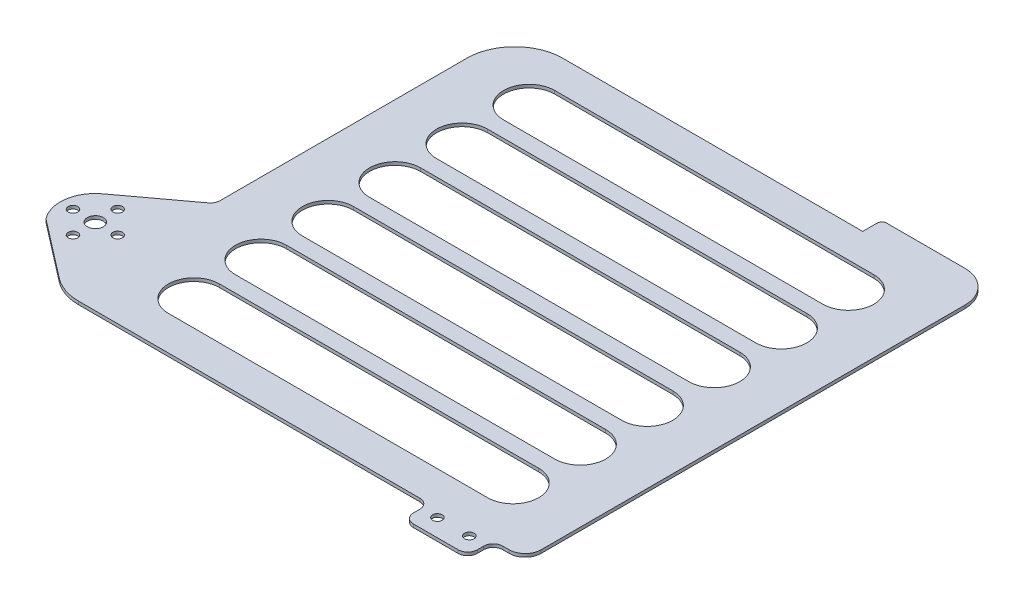
SolidWorks part; units mm, degrees
material "A-玻璃纤维"
ref_plane "前视基准面" through (0, 0, 0) normal (0, 0, 1) x (1, 0, 0)
ref_plane "上视基准面" through (0, 0, 0) normal (0, 1, 0) x (1, 0, 0)
ref_plane "右视基准面" through (0, 0, 0) normal (1, 0, 0) x (0, 0, -1)
sketch "草图1" plane through (0, 0, 0) normal (0, 1, 0) x (1, 0, 0)
  line L1 (-72.5, 70.87) -> (72.5, 70.87)
  line L2 (-72.5, 70.87) -> (-72.5, -70.87)
  line L3 (-72.5, -70.87) -> (72.5, -70.87)
  line L4 (72.5, 70.87) -> (72.5, -70.87)
  line L5 (0, -70.87) -> (0, 70.87) construction
  line L6 (-72.5, 0) -> (72.5, 0) construction
  point P0 (0, 0)
  dimension "D1" = 145
  dimension "D2" = 141.74
extrude "凸台-拉伸1" add sketch "草图1" along normal blind 1
fillet "圆角1" radius 15 1 edges at (-72.5, 0.5, -70.87)
sketch "草图2" plane through (0, 1, 0) normal (0, 1, 0) x (1, 0, 0)
  line L0 (-72.5, -70.87) -> (72.5, -70.87) construction
  line L1 (-72.5, 55.87) -> (-72.5, -70.87) construction
  line L2 (-92.7479, -37.9812) -> (-72.5, -22.9812)
  line L3 (-94.8039, -53.6736) -> (-72.5, -81.6736)
  line L4 (-72.5, -22.9812) -> (-72.5, -81.6736)
  arc A0 (-92.7479, -37.9812) -> (-94.8039, -53.6736) centre (-86.2, -46.82) ccw
  dimension "D1" = 24.05
  dimension "D2" = 13.7
  dimension "D3" = 22
  dimension "D4" = 15
  dimension "D5" = 28
extrude "凸台-拉伸2" add sketch "草图2" against normal blind 1
sketch "草图3" plane through (0, 1, 0) normal (0, 1, 0) x (1, 0, 0)
  circle A0 centre (-86.2, -46.82) radius 2.5
  circle A1 centre (-93.2, -46.82) radius 1.5
  dimension "D1" = 5
  dimension "D2" = 3
  dimension "D3" = 7
extrude "切除-拉伸1" cut sketch "草图3" against normal through all
pattern_circular "阵列(圆周)1" count 4 over 360 about axis through (-86.2, 0, 46.82) along (0, 1, 0) of "切除-拉伸1"
sketch "草图4" plane through (0, 1, 0) normal (0, 1, 0) x (1, 0, 0)
  line L0 (-72.5, -70.87) -> (-94.8039, -53.6736)
  line L1 (-94.8039, -53.6736) -> (-72.5, -88.8628)
  line L2 (-72.5, -88.8628) -> (-72.5, -70.87)
  dimension "D1" = 20
extrude "切除-拉伸2" cut sketch "草图4" against normal through all
fillet "圆角2" radius 15 1 edges at (-72.5, 0.5, 70.87)
fillet "圆角3" radius 3 1 edges at (-72.5, 0.5, 22.9812)
sketch "草图5" plane through (0, 1, 0) normal (0, 1, 0) x (1, 0, 0)
  line L0 (-50, 52.87) -> (50, 52.87) construction
  line L1 (-50, 60.87) -> (50, 60.87)
  line L2 (-50, 44.87) -> (50, 44.87)
  line L3 (72.5, 70.87) -> (-57.5, 70.87) construction
  line L4 (-50, 31.87) -> (50, 31.87) construction
  line L5 (-50, 39.87) -> (50, 39.87)
  line L6 (-50, 23.87) -> (50, 23.87)
  line L7 (-50, 10.87) -> (50, 10.87) construction
  line L8 (-50, 18.87) -> (50, 18.87)
  line L9 (-50, 2.87) -> (50, 2.87)
  line L10 (-50, -10.13) -> (50, -10.13) construction
  line L11 (-50, -2.13) -> (50, -2.13)
  line L12 (-50, -18.13) -> (50, -18.13)
  line L13 (-50, -31.13) -> (50, -31.13) construction
  line L14 (-50, -23.13) -> (50, -23.13)
  line L15 (-50, -39.13) -> (50, -39.13)
  line L16 (-50, -52.13) -> (50, -52.13) construction
  line L17 (-50, -44.13) -> (50, -44.13)
  line L18 (-50, -60.13) -> (50, -60.13)
  arc A0 (-50, 60.87) -> (-50, 44.87) centre (-50, 52.87) ccw
  arc A1 (50, 44.87) -> (50, 60.87) centre (50, 52.87) ccw
  arc A2 (-50, 39.87) -> (-50, 23.87) centre (-50, 31.87) ccw
  arc A3 (50, 23.87) -> (50, 39.87) centre (50, 31.87) ccw
  arc A4 (-50, 18.87) -> (-50, 2.87) centre (-50, 10.87) ccw
  arc A5 (50, 2.87) -> (50, 18.87) centre (50, 10.87) ccw
  arc A6 (-50, -2.13) -> (-50, -18.13) centre (-50, -10.13) ccw
  arc A7 (50, -18.13) -> (50, -2.13) centre (50, -10.13) ccw
  arc A8 (-50, -23.13) -> (-50, -39.13) centre (-50, -31.13) ccw
  arc A9 (50, -39.13) -> (50, -23.13) centre (50, -31.13) ccw
  arc A10 (-50, -44.13) -> (-50, -60.13) centre (-50, -52.13) ccw
  arc A11 (50, -60.13) -> (50, -44.13) centre (50, -52.13) ccw
  point P2 (0, 52.87)
  point P14 (0, 31.87)
  point P21 (0, 10.87)
  point P28 (0, -10.13)
  point P35 (0, -31.13)
  point P42 (0, -52.13)
  dimension "D1" = 100
  dimension "D2" = 10
  dimension "D3" = 16
  dimension "D4" = 6
extrude "切除-拉伸3" cut sketch "草图5" against normal through all
sketch "草图6" plane through (0, 0, -70.87) normal (0, 0, -1) x (-1, 0, 0)
  line L0 (-72.5, 1) -> (57.5, 1) construction
  line L1 (-72.5, 0) -> (-36.5, 0)
  line L2 (-72.5, 0) -> (-72.5, 1)
  line L3 (-72.5, 1) -> (-36.5, 1)
  line L4 (-36.5, 0) -> (-36.5, 1)
  dimension "D1" = 36
extrude "凸台-拉伸3" add sketch "草图6" along normal blind 6
fillet "圆角4" radius 10 1 edges at (72.5, 0.5, -76.87)
fillet "圆角5" radius 1.5 1 edges at (36.5, 0.5, -76.87)
sketch "草图8" plane through (0, 1, 0) normal (0, 1, 0) x (1, 0, 0)
  line L0 (72.5, -70.87) -> (72.5, 66.87) construction
  line L1 (62.5, -70.87) -> (42.5, -70.87)
  line L2 (62.5, -70.87) -> (62.5, -78.87)
  line L3 (62.5, -78.87) -> (42.5, -78.87)
  line L4 (42.5, -70.87) -> (42.5, -78.87)
  line L5 (-67.3889, -70.87) -> (72.5, -70.87) construction
  circle A0 centre (47.5048, -73.37) radius 1.5
  circle A1 centre (57.5048, -73.37) radius 1.5
  dimension "D4" = 3
  dimension "D5" = 3
  dimension "D6" = 10
  dimension "D8" = 5.0048
  dimension "D1" = 20
  dimension "D2" = 10
  dimension "D3" = 8
  dimension "D7" = 2.5
extrude "凸台-拉伸5" add sketch "草图8" against normal blind 1
fillet "圆角8" radius 3 4 edges at (62.5, 0.5, 70.87) (62.5, 0.5, 78.87) (42.5, 0.5, 78.87) (42.5, 0.5, 70.87)
fillet "圆角9" radius 5 1 edges at (72.5, 0.5, 70.87)
